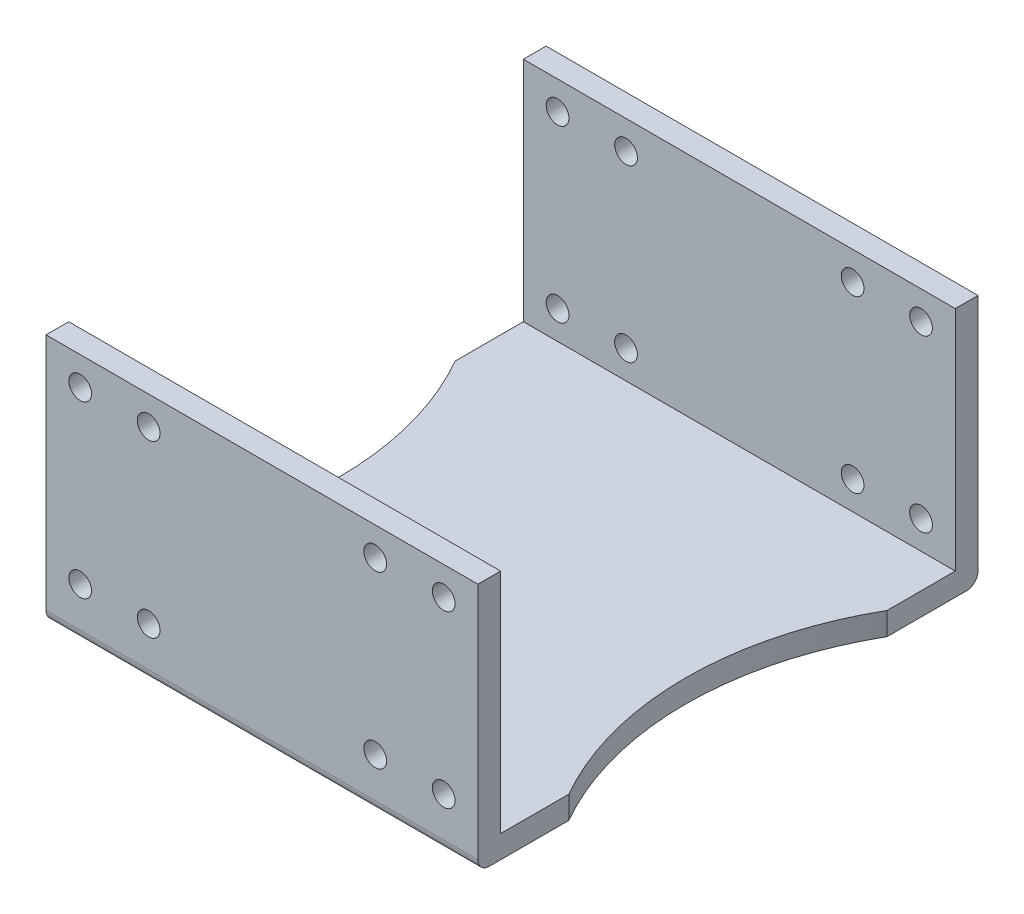
SolidWorks part; units mm, degrees
ref_plane "正面" through (0, 0, 0) normal (0, 0, 1) x (1, 0, 0)
ref_plane "平面" through (0, 0, 0) normal (0, 1, 0) x (1, 0, 0)
ref_plane "右側面" through (0, 0, 0) normal (1, 0, 0) x (0, 0, -1)
sketch "ｽｹｯﾁ1" plane through (0, 0, 0) normal (1, 0, 0) x (0, 0, -1)
  line L0 (-22, 0) -> (22, 0)
  line L1 (55, 0) -> (-55, 0) construction
  line L2 (22, 0) -> (22, 22)
  line L3 (22, 22) -> (20, 22)
  line L4 (20, 22) -> (20, 2)
  line L5 (20, 2) -> (-20, 2)
  line L6 (0, 55) -> (0, -55) construction
  line L7 (0, 2) -> (0, 0)
  line L8 (-20, 22) -> (-20, 2)
  line L9 (-22, 22) -> (-20, 22)
  line L10 (-22, 0) -> (-22, 22)
extrude "ﾎﾞｽ - 押し出し1" add sketch "ｽｹｯﾁ1" along normal blind 38 contours L10 L9 L8 L5 L4 L3 L2 L0
ref_plane "平面1" through (0, 12, 0) normal (0, 1, 0) x (1, 0, 0)
sketch "ｽｹｯﾁ3" plane through (0, 12, 0) normal (0, 1, 0) x (1, 0, 0)
  line L0 (0, 20.0447) -> (38, -20)
  line L1 (0, -12.1) -> (0, 12.1) construction
  line L2 (0, -20) -> (38, 20)
  line L3 (19, 0.0223) -> (19, -20)
  line L4 (38, -20) -> (0, -20) construction
  line L5 (38, 20) -> (38, 14)
  line L6 (38, 20) -> (38, -20) construction
  line L7 (38, -20) -> (38, -14)
  line L8 (0, 14) -> (0, -14)
  line L9 (38, 14) -> (38, -14)
  arc A0 (38, 14) -> (38, -14) centre (62.417, 0) ccw
  arc A1 (0, 14) -> (0, -14) centre (-24.417, 0) cw
extrude "ｶｯﾄ - 押し出し1" cut sketch "ｽｹｯﾁ3" against normal blind 38 contours A1 L8 | L9 A0
sketch "ｽｹｯﾁ4" plane through (0, 0, 22) normal (0, 0, 1) x (1, 0, 0)
  line L1 (22, 12) -> (-22, 12) construction
  circle A0 centre (3.0104, 19.5) radius 1
  circle A1 centre (9.0332, 19.5) radius 1
  circle A2 centre (3.0104, 4.5) radius 1
  circle A3 centre (9.0332, 4.5) radius 1
  circle A4 centre (28.9668, 19.5) radius 1
  circle A5 centre (34.9896, 19.5) radius 1
  circle A6 centre (34.9896, 4.5) radius 1
  circle A7 centre (28.9668, 4.5) radius 1
extrude "ｶｯﾄ - 押し出し3" cut sketch "ｽｹｯﾁ4" against normal blind 68
fillet "ﾌｨﾚｯﾄ1" radius 1 2 edges at (19, 0, -22) (19, 0, 22)
